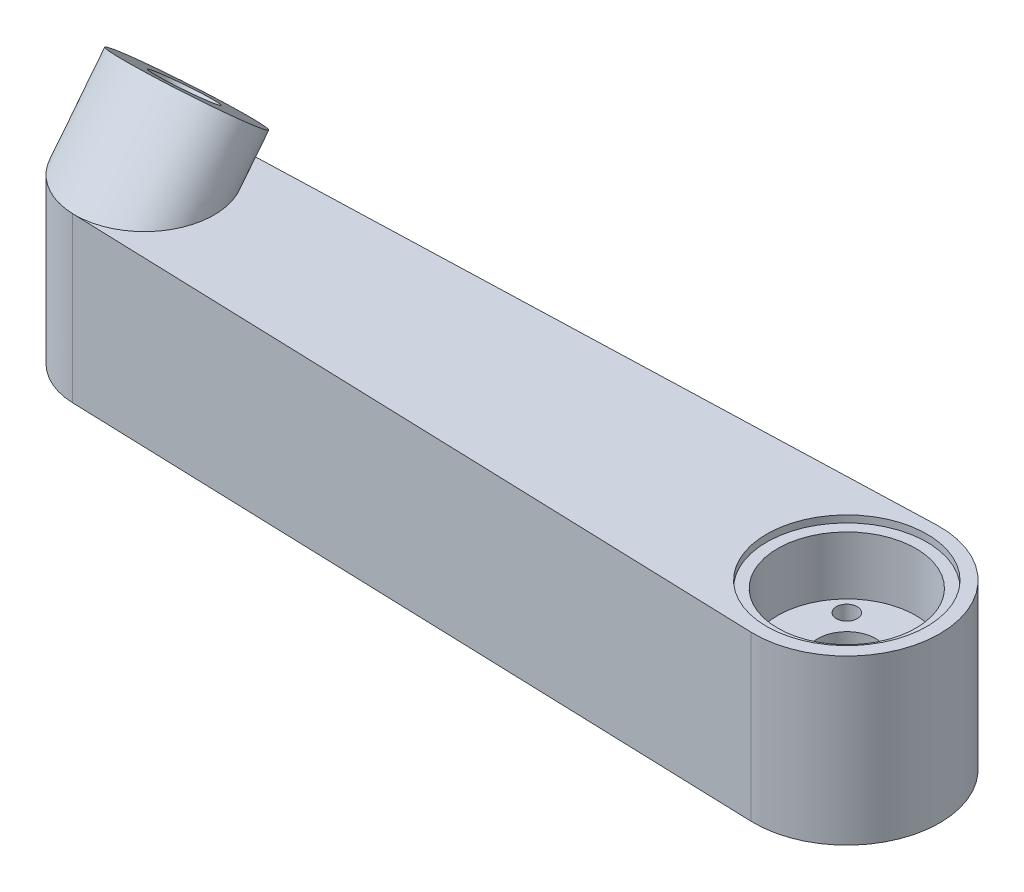
SolidWorks part; units mm, degrees
ref_plane "Front Plane" through (0, 0, 0) normal (0, 0, 1) x (1, 0, 0)
ref_plane "Top Plane" through (0, 0, 0) normal (0, 1, 0) x (1, 0, 0)
ref_plane "Right Plane" through (0, 0, 0) normal (1, 0, 0) x (0, 0, -1)
sketch "Sketch1" plane through (0, 0, 0) normal (0, 1, 0) x (1, 0, 0)
  line L0 (-62.1505, 0) -> (-1.6505, 0) construction
  line L1 (-62.3488, 5.9967) -> (-1.9149, 7.9956)
  line L2 (-62.3488, -5.9967) -> (-1.9149, -7.9956)
  arc A0 (-1.9149, -7.9956) -> (-1.9149, 7.9956) centre (-1.6505, 0) ccw
  arc A1 (-62.3488, 5.9967) -> (-62.3488, -5.9967) centre (-62.1505, 0) ccw
  dimension "D1" = 12
  dimension "D2" = 16
  dimension "D3" = 60.5
extrude "Boss-Extrude1" add sketch "Sketch1" along normal blind 14.11
sketch "Sketch2" plane through (0, 14.11, 0) normal (0, 1, 0) x (1, 0, 0)
  circle A0 centre (-1.6505, 0) radius 5.95
  dimension "D1" = 11.9
extrude "Cut-Extrude1" cut sketch "Sketch2" against normal blind 5.6
sketch "Sketch3" plane through (0, 14.11, 0) normal (0, 1, 0) x (1, 0, 0)
  circle A0 centre (-1.6505, 0) radius 6.9
  dimension "D1" = 13.8
extrude "Cut-Extrude2" cut sketch "Sketch3" against normal blind 0.6
sketch "Sketch4" plane through (0, 8.51, 0) normal (0, 1, 0) x (1, 0, 0)
  circle A0 centre (-1.6505, 0) radius 2.5
  dimension "D1" = 5
extrude "Cut-Extrude3" cut sketch "Sketch4" against normal through all
sketch "Sketch5" plane through (0, 8.51, 0) normal (0, 1, 0) x (1, 0, 0)
  line L0 (-1.6505, 0) -> (-8.0451, 6.3946) construction
  circle A0 centre (-4.8325, 3.182) radius 0.9
  dimension "D2" = 1.8
  dimension "D1" = 4.5
extrude "Cut-Extrude4" cut sketch "Sketch5" against normal blind 4.4
sketch "Sketch6" plane through (0, 0, 0) normal (0, -1, 0) x (1, 0, 0)
  circle A0 centre (-1.6505, 0) radius 6
  dimension "D1" = 12
extrude "Cut-Extrude6" cut sketch "Sketch6" against normal blind 2.5
sketch "Sketch10" plane through (0, 2.5, 0) normal (0, -1, 0) x (1, 0, 0)
  line L0 (0.7577, -0.6714) -> (4.3472, -0.1669)
  line L1 (-7.6482, 0.1669) -> (-4.0586, 0.6714)
  line L2 (-7.3698, -1.8136) -> (-3.7803, -1.3092)
  line L4 (-4.0586, 0.6714) -> (-7.6482, 0.1669) construction
  line L5 (4.0689, 1.8136) -> (0.4793, 1.3092) construction
  line L6 (0.4793, 1.3092) -> (4.0689, 1.8136)
  arc A0 (-4.0586, 0.6714) -> (-3.7803, -1.3092) centre (-1.6505, 0) ccw
  arc A1 (-7.6482, 0.1669) -> (-7.3698, -1.8136) centre (-1.6505, 0) ccw
  arc A2 (4.3472, -0.1669) -> (4.0689, 1.8136) centre (-1.6505, 0) ccw
  arc A3 (0.7577, -0.6714) -> (0.4793, 1.3092) centre (-1.6505, 0) ccw
  point P0 (-1.6505, 0)
  point P3 (-1.6505, 0)
extrude "Boss-Extrude5" add sketch "Sketch10" along normal blind 0.4
sketch "Sketch11" plane through (-0.2663, 0, -8.0502) normal (-0.0331, 0, -0.9995) x (-0.9995, 0, 0.0331)
  line L1 (8.6496, 0) -> (68.1165, 2.2207)
  line L2 (68.1165, -9.4038) -> (68.1165, 2.2207)
  line L3 (68.1165, -9.4038) -> (8.6496, 0)
  line L4 (1.6496, 0) -> (62.1165, 0) construction
  dimension "D1" = 15
sketch "Sketch12" plane through (0, 14.11, 0) normal (0, 1, 0) x (1, 0, 0)
  line L0 (-58.8453, 6.1126) -> (-58.8453, -19.139)
  line L1 (-1.9149, 7.9956) -> (-62.3488, 5.9967) construction
ref_plane "Plane1" through (-0.3397, 12.2462, -10.2702) normal (-0.0212, 0.766, -0.6424) x (0.9997, 0.0212, -0.0077)
ref_plane "Plane2" through (-0.3822, 13.7783, -11.555) normal (-0.0212, 0.766, -0.6424) x (0.9997, 0.0212, -0.0077)
sketch "Sketch13" plane through (-0.3822, 13.7783, -11.555) normal (-0.0212, 0.766, -0.6424) x (0.9997, 0.0212, -0.0077)
  ellipse E1 centre (-61.8348, -9.5452) end of major axis (-67.8315, -9.7435) minor radius 4.5963
extrude "Boss-Extrude6" add sketch "Sketch13" against normal up to surface (5.8567 mm away)
sketch "Sketch14" plane through (-0.3822, 13.7783, -11.555) normal (-0.0212, 0.766, -0.6424) x (0.9998, 0.0163, -0.0137)
  circle A0 centre (-62.0962, -9.0946) radius 2.5
  dimension "D1" = 5
extrude "Cut-Extrude8" cut sketch "Sketch14" against normal blind 8
